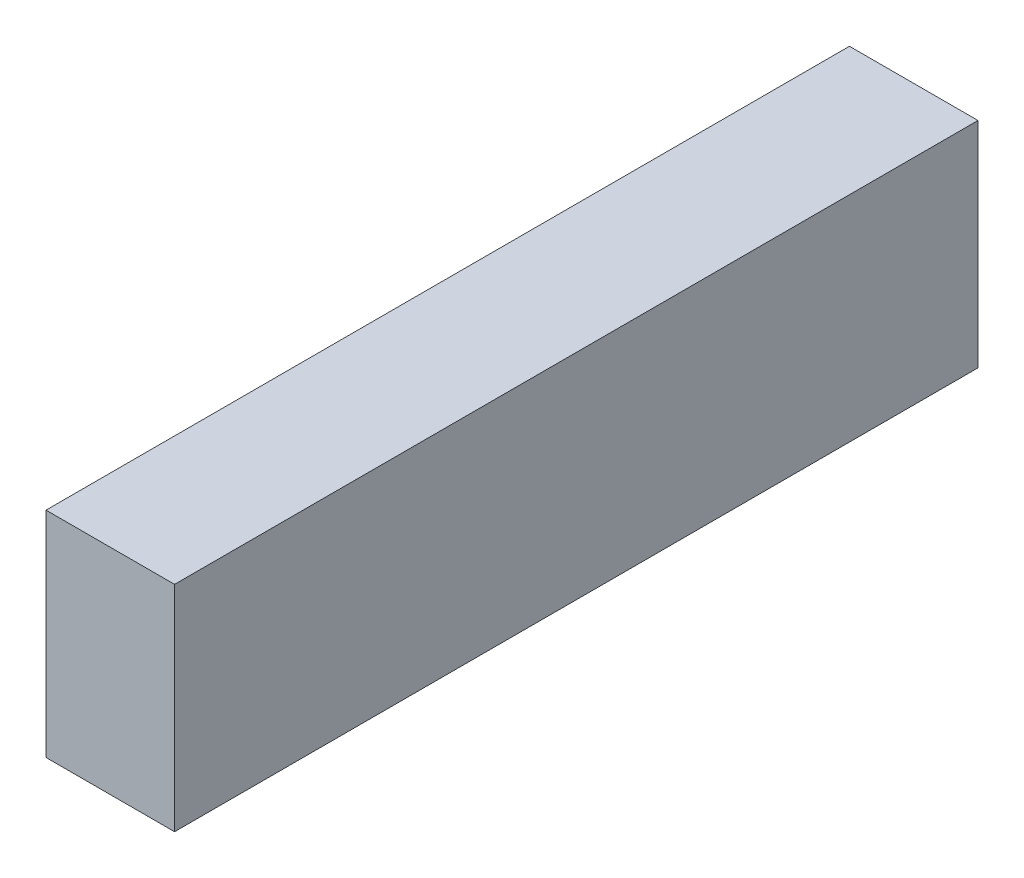
SolidWorks part; units mm, degrees
ref_plane "Front Plane" through (0, 0, 0) normal (0, 0, 1) x (1, 0, 0)
ref_plane "Top Plane" through (0, 0, 0) normal (0, 1, 0) x (1, 0, 0)
ref_plane "Right Plane" through (0, 0, 0) normal (1, 0, 0) x (0, 0, -1)
sketch "Sketch1" plane through (0, 0, 0) normal (0, 0, 1) x (1, 0, 0)
  line L1 (-6, -10) -> (6, -10)
  line L2 (-6, -10) -> (-6, 10)
  line L3 (-6, 10) -> (6, 10)
  line L4 (6, -10) -> (6, 10)
  line L5 (-6, -10) -> (6, 10) construction
  line L6 (-6, 10) -> (6, -10) construction
  point P0 (0, 0)
  dimension "D1" = 20
  dimension "D2" = 12
extrude "Boss-Extrude1" add sketch "Sketch1" along normal blind 75
